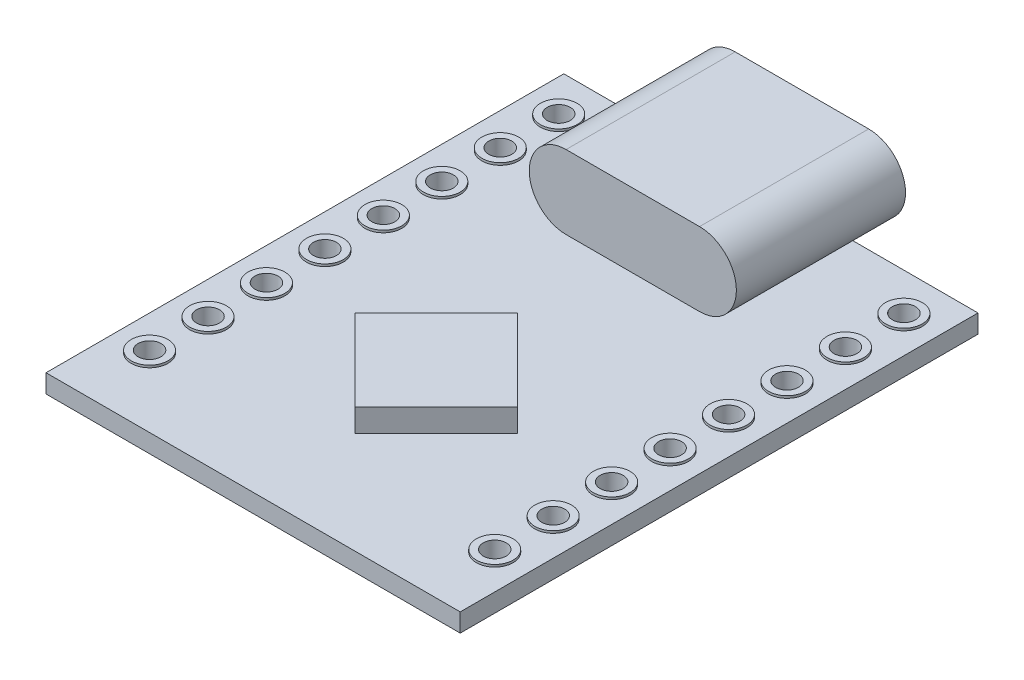
SolidWorks part; units mm, degrees
ref_plane "Front Plane" through (0, 0, 0) normal (0, 0, 1) x (1, 0, 0)
ref_plane "Top Plane" through (0, 0, 0) normal (0, 1, 0) x (1, 0, 0)
ref_plane "Right Plane" through (0, 0, 0) normal (1, 0, 0) x (0, 0, -1)
sketch "Sketch1" plane through (0, 0, 0) normal (0, 1, 0) x (1, 0, 0)
  line L1 (-9, 11.25) -> (9, 11.25)
  line L2 (-9, 11.25) -> (-9, -11.25)
  line L3 (-9, -11.25) -> (9, -11.25)
  line L4 (9, 11.25) -> (9, -11.25)
  line L5 (-9, 11.25) -> (9, -11.25) construction
  line L6 (-9, -11.25) -> (9, 11.25) construction
  point P0 (0, 0)
  dimension "D1" = 22.5
  dimension "D2" = 18
extrude "Boss-Extrude1" add sketch "Sketch1" along normal mid plane 0.8
sketch "Sketch2" plane through (0, 0.4, 0) normal (0, 1, 0) x (1, 0, 0)
  line L0 (0, 11.9354) -> (0, -12.272) construction
  line L1 (7.5, -8.75) -> (0, -8.75) construction
  line L2 (-9, -11.25) -> (9, -11.25) construction
  line L3 (8, -8.25) -> (8, -11.25) construction
  line L4 (9, -11.25) -> (9, 11.25) construction
  circle A0 centre (7.5, -8.25) radius 0.5
  circle A1 centre (-7.5, -8.25) radius 0.5
  circle A2 centre (-7.5, -5.71) radius 0.5
  circle A3 centre (7.5, -5.71) radius 0.5
  circle A4 centre (-7.5, -3.17) radius 0.5
  circle A5 centre (7.5, -3.17) radius 0.5
  circle A6 centre (-7.5, -0.63) radius 0.5
  circle A7 centre (7.5, -0.63) radius 0.5
  circle A8 centre (-7.5, 1.91) radius 0.5
  circle A9 centre (7.5, 1.91) radius 0.5
  circle A10 centre (-7.5, 4.45) radius 0.5
  circle A11 centre (7.5, 4.45) radius 0.5
  circle A12 centre (-7.5, 6.99) radius 0.5
  circle A13 centre (7.5, 6.99) radius 0.5
  circle A14 centre (-7.5, 9.53) radius 0.5
  circle A15 centre (7.5, 9.53) radius 0.5
  dimension "D1" = 2.5
  dimension "D2" = 1
  dimension "D3" = 1
  dimension "D5" = 2.54
  dimension "D4" = 8
extrude "Cut-Extrude1" cut sketch "Sketch2" against normal through all both and the other way through all
sketch "Sketch3" plane through (0, 0, -11.25) normal (0, 0, -1) x (-1, 0, 0)
  line L0 (-2.9, 2) -> (2.9, 2) construction
  line L1 (-2.9, 3.6) -> (2.9, 3.6)
  line L2 (-2.9, 0.4) -> (2.9, 0.4)
  line L3 (-9, 0.4) -> (9, 0.4) construction
  line L4 (4.5, 2) -> (4.5, -1.3796) construction
  line L5 (-4.5, 2) -> (-4.5, -1.8178) construction
  arc A0 (-2.9, 3.6) -> (-2.9, 0.4) centre (-2.9, 2) ccw
  arc A1 (2.9, 0.4) -> (2.9, 3.6) centre (2.9, 2) ccw
  point P2 (0, 2)
  point P13 (0, 0)
  dimension "D1" = 3.2
  dimension "D2" = 9
extrude "Boss-Extrude2" add sketch "Sketch3" along normal blind 1.35 and the other way blind 6 contours A0 L2 A1 L1
sketch "Sketch4" plane through (0, 0, -12.6) normal (0, 0, -1) x (-1, 0, 0)
  line L4 (-2.9, 0.8) -> (2.9, 0.8)
  line L5 (2.9, 3.2) -> (-2.9, 3.2)
  line L6 (-2.9, 0.8) -> (2.9, 0.8)
  line L7 (2.9, 3.2) -> (-2.9, 3.2)
  arc A4 (-2.9, 3.2) -> (-2.9, 0.8) centre (-2.9, 2) ccw
  arc A5 (2.9, 0.8) -> (2.9, 3.2) centre (2.9, 2) ccw
  arc A6 (-2.9, 3.2) -> (-2.9, 0.8) centre (-2.9, 2) ccw
  arc A7 (2.9, 0.8) -> (2.9, 3.2) centre (2.9, 2) ccw
  dimension "D1" = 0.4
extrude "Cut-Extrude2" cut sketch "Sketch4" against normal blind 7 and the other way through all
sketch "Sketch5" plane through (0, 0.4, 0) normal (0, 1, 0) x (1, 0, 0)
  line L0 (-3.5428, -3.2855) -> (-0.0073, -6.8211)
  line L1 (-3.5428, -3.2855) -> (-0.0073, 0.25)
  line L2 (-0.0073, -6.8211) -> (3.5283, -3.2855)
  line L3 (-0.0073, 0.25) -> (3.5283, -3.2855)
  line L4 (2.9, 5.25) -> (-2.9, 5.25) construction
  point P4 (0, 0)
  dimension "D1" = 5
  dimension "D2" = 5
extrude "Boss-Extrude3" add sketch "Sketch5" along normal blind 1
sketch "Sketch6" plane through (0, 0.4, 0) normal (0, 1, 0) x (1, 0, 0)
  line L0 (0, 0) -> (0, -9.0367) construction
  circle A0 centre (-7.5, -8.25) radius 0.8
  circle A1 centre (-7.5, -8.25) radius 0.5 construction
  circle A2 centre (-7.5, -8.25) radius 0.5
  circle A3 centre (7.5, -8.25) radius 0.8
  circle A4 centre (7.5, -8.25) radius 0.5
  circle A5 centre (7.5, -5.71) radius 0.8
  circle A6 centre (7.5, -5.71) radius 0.5
  circle A7 centre (-7.5, -5.71) radius 0.8
  circle A8 centre (-7.5, -5.71) radius 0.5
  circle A9 centre (7.5, -3.17) radius 0.8
  circle A10 centre (7.5, -3.17) radius 0.5
  circle A11 centre (-7.5, -3.17) radius 0.8
  circle A12 centre (-7.5, -3.17) radius 0.5
  circle A13 centre (7.5, -0.63) radius 0.8
  circle A14 centre (7.5, -0.63) radius 0.5
  circle A15 centre (-7.5, -0.63) radius 0.8
  circle A16 centre (-7.5, -0.63) radius 0.5
  circle A17 centre (7.5, 1.91) radius 0.8
  circle A18 centre (7.5, 1.91) radius 0.5
  circle A19 centre (-7.5, 1.91) radius 0.8
  circle A20 centre (-7.5, 1.91) radius 0.5
  circle A21 centre (7.5, 4.45) radius 0.8
  circle A22 centre (7.5, 4.45) radius 0.5
  circle A23 centre (-7.5, 4.45) radius 0.8
  circle A24 centre (-7.5, 4.45) radius 0.5
  circle A25 centre (7.5, 6.99) radius 0.8
  circle A26 centre (7.5, 6.99) radius 0.5
  circle A27 centre (-7.5, 6.99) radius 0.8
  circle A28 centre (-7.5, 6.99) radius 0.5
  circle A29 centre (7.5, 9.53) radius 0.8
  circle A30 centre (7.5, 9.53) radius 0.5
  circle A31 centre (-7.5, 9.53) radius 0.8
  circle A32 centre (-7.5, 9.53) radius 0.5
  dimension "D1" = 1.6
  dimension "D2" = 8
extrude "Boss-Extrude4" add sketch "Sketch6" along normal blind 0.1 and the other way blind 0.9
